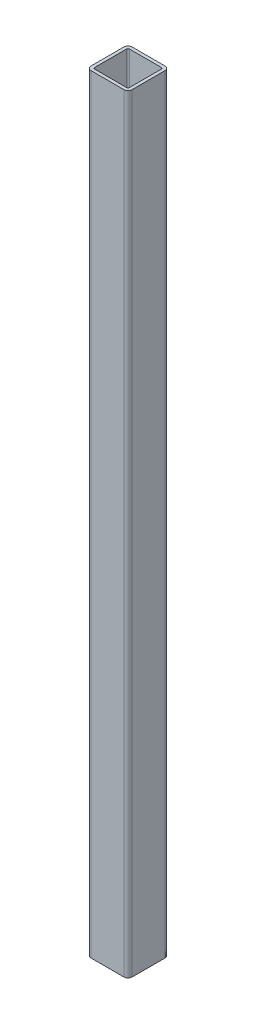
SolidWorks part; units mm, degrees
material "6061-T6 (SS)"
ref_plane "Front Plane" through (0, 0, 0) normal (0, 0, 1) x (1, 0, 0)
ref_plane "Top Plane" through (0, 0, 0) normal (0, 1, 0) x (1, 0, 0)
ref_plane "Right Plane" through (0, 0, 0) normal (1, 0, 0) x (0, 0, -1)
sketch "Extrude sketch 1" plane through (0, 0, 0) normal (0, 1, 0) x (1, 0, 0)
  line L0 (20, 16) -> (20, -16)
  line L1 (16, -20) -> (-16, -20)
  line L2 (-20, -16) -> (-20, 16)
  line L3 (-16, 20) -> (16, 20)
  line L4 (17, 15.5) -> (17, -15.5)
  line L5 (15.5, -17) -> (-15.5, -17)
  line L6 (-17, -15.5) -> (-17, 15.5)
  line L7 (-15.5, 17) -> (15.5, 17)
  arc A0 (20, -16) -> (16, -20) centre (16, -16) cw
  arc A1 (-16, -20) -> (-20, -16) centre (-16, -16) cw
  arc A2 (-20, 16) -> (-16, 20) centre (-16, 16) cw
  arc A3 (16, 20) -> (20, 16) centre (16, 16) cw
  arc A4 (17, -15.5) -> (15.5, -17) centre (15.5, -15.5) cw
  arc A5 (-15.5, -17) -> (-17, -15.5) centre (-15.5, -15.5) cw
  arc A6 (-17, 15.5) -> (-15.5, 17) centre (-15.5, 15.5) cw
  arc A7 (15.5, 17) -> (17, 15.5) centre (15.5, 15.5) cw
  dimension "D1" = 4
  dimension "D2" = 1.5
  dimension "D3" = 3
  dimension "D4" = 37
  dimension "D5" = 40
  dimension "D6" = 3
extrude "Extrude 1" add sketch "Extrude sketch 1" along normal blind 750 from offset 375 separate body
